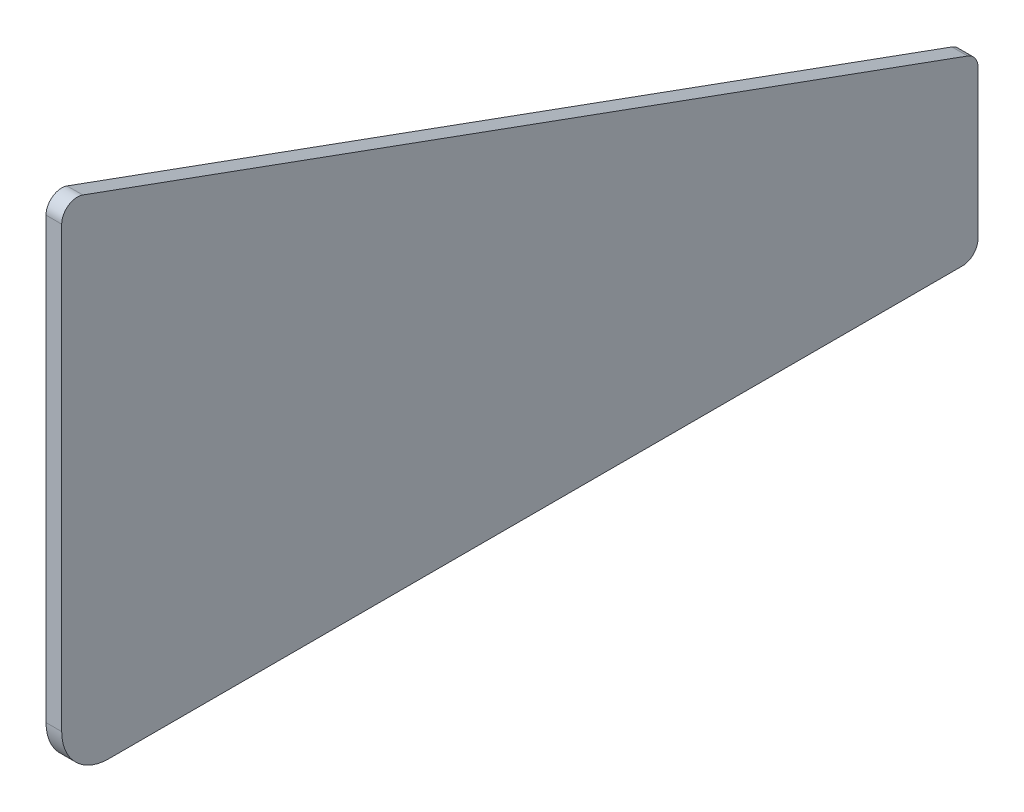
SolidWorks part; units mm, degrees
material "Hexcel AS4C (3000 Filaments)"
ref_plane "Front Plane" through (0, 0, 0) normal (0, 0, 1) x (1, 0, 0)
ref_plane "Top Plane" through (0, 0, 0) normal (0, 1, 0) x (1, 0, 0)
ref_plane "Right Plane" through (0, 0, 0) normal (1, 0, 0) x (0, 0, -1)
sketch "Sketch1" plane through (0, 0, 0) normal (1, 0, 0) x (0, 0, -1)
  line L0 (0, -14.2815) -> (0, -294.2815)
  line L1 (0, 29.2892) -> (0, -29.2892) construction
  line L2 (30, -324.2815) -> (573.8156, -324.2815)
  line L3 (583.8156, -314.2815) -> (583.8156, -219.4936)
  line L4 (577.2358, -210.0966) -> (13.4202, -4.8846)
  arc A0 (30, -324.2815) -> (0, -294.2815) centre (30, -294.2815) cw
  arc A1 (573.8156, -324.2815) -> (583.8156, -314.2815) centre (573.8156, -314.2815) ccw
  arc A2 (583.8156, -219.4936) -> (577.2358, -210.0966) centre (573.8156, -219.4936) ccw
  arc A3 (13.4202, -4.8846) -> (0, -14.2815) centre (10, -14.2815) ccw
  point P9 (0, -324.2815)
  point P16 (0, 0)
  dimension "D2" = 30
  dimension "D3" = 10
  dimension "D1" = 70
  dimension "D4" = 280
  dimension "D5" = 600
extrude "Boss-Extrude1" add sketch "Sketch1" along normal blind 10
sketch "Sketch2" plane through (10, 0, 0) normal (1, 0, 0) x (0, 0, -1)
  arc A0 (23.1622, -218.0173) -> (26.7381, -200.3183) centre (26.5742, -209.4959) cw
  arc A1 (549.474, -291.831) -> (546.1549, -257.731) centre (546.1581, -274.9423) ccw
  arc A2 (26.9502, -47.7372) -> (35.1249, -39.1544) centre (32.8168, -45.1404) cw
  arc A3 (356.3201, -205.3163) -> (353.1695, -171.1817) centre (353.1695, -188.3944) ccw
  spline S0 degree 3 poles (23.1622, -218.0173) (143.0808, -266.0342) (284.6699, -324.5722) (474.7501, -306.5023) (549.474, -291.831) knots 0 0 0 0 0.576112 1 1 1 1
  spline S1 degree 3 poles (26.7381, -200.3183) (45.9144, -200.6608) (151.3211, -255.5104) (414.8803, -286.3851) (542.4311, -257.7317) (546.1549, -257.731) knots 0 0 0 0 0.560935 0.660935 1 1 1 1
  spline S2 degree 3 poles (26.9502, -47.7372) (35.3127, -66.6296) (121.3965, -217.9891) (352.8389, -205.9644) (356.3201, -205.3163) knots 0 0 0 0 0.590315 1 1 1 1
  spline S3 degree 3 poles (35.1249, -39.1544) (50.603, -45.1224) (99.0425, -170.6619) (331.224, -171.1817) (353.1695, -171.1817) knots 0 0 0 0 0.639196 1 1 1 1
sketch "Sketch3" plane through (0, 0, 0) normal (-1, 0, 0) x (0, 0, 1)
  arc A2 (-23.1622, -218.0173) -> (-26.7381, -200.3183) centre (-26.5742, -209.4959) ccw
  arc A3 (-546.1549, -257.731) -> (-549.474, -291.831) centre (-546.1581, -274.9423) ccw
  arc A4 (-23.1622, -218.0173) -> (-26.7381, -200.3183) centre (-26.5742, -209.4959) ccw
  arc A5 (-546.1549, -257.731) -> (-549.474, -291.831) centre (-546.1581, -274.9423) ccw
  arc A6 (-26.9502, -47.7372) -> (-35.1249, -39.1544) centre (-32.8168, -45.1404) ccw
  arc A7 (-353.1695, -171.1817) -> (-356.3201, -205.3163) centre (-353.1695, -188.3944) ccw
  arc A8 (-26.9502, -47.7372) -> (-35.1249, -39.1544) centre (-32.8168, -45.1404) ccw
  arc A9 (-353.1695, -171.1817) -> (-356.3201, -205.3163) centre (-353.1695, -188.3944) ccw
  spline S2 degree 3 poles (-2896.6142, -4288.4219) (3.574, 379.1035) (337.9044, -198.2) (-671.2842, -316.4215) (-1165.7534, 76.4704) (4167.8421, -1921.4128) knots -1.856226 -1.856226 -1.856226 -1.856226 0.560935 0.660935 1.972851 1.972851 1.972851 1.972851 only from (-26.7381, -200.3183) to (-546.1549, -257.731)
  spline S3 degree 3 poles (4297.6783, -1440.9535) (-2101.1476, 528.1742) (-39.3944, -1013.16) (229.8904, 277.3112) (4925.3757, 333.413) knots -3.073366 -3.073366 -3.073366 -3.073366 0.423888 3.006514 3.006514 3.006514 3.006514 only from (-549.474, -291.831) to (-23.1622, -218.0173)
  spline S4 degree 3 poles (-26.7381, -200.3183) (-45.9144, -200.6608) (-151.3211, -255.5104) (-414.8803, -286.3851) (-542.4311, -257.7317) (-546.1549, -257.731) knots 0 0 0 0 0.560935 0.660935 1 1 1 1
  spline S5 degree 3 poles (-549.474, -291.831) (-474.7501, -306.5023) (-284.6699, -324.5722) (-143.0808, -266.0342) (-23.1622, -218.0173) knots 0 0 0 0 0.423888 1 1 1 1
  spline S6 degree 3 poles (1154.6406, -4892.5213) (-500.1842, 847.1931) (679.6519, -597.1648) (-1151.2382, 7.0013) (4611.9466, -753.8783) knots -1.849916 -1.849916 -1.849916 -1.849916 0.639196 2.198 2.198 2.198 2.198 only from (-35.1249, -39.1544) to (-353.1695, -171.1817)
  spline S7 degree 3 poles (4570.7768, -1047.92) (-1095.3741, 46.8314) (476.6072, -749.5305) (-175.5635, 954.0689) (-848.8771, -4973.4503) knots -1.172462 -1.172462 -1.172462 -1.172462 0.409685 2.739203 2.739203 2.739203 2.739203 only from (-356.3201, -205.3163) to (-26.9502, -47.7372)
  spline S8 degree 3 poles (-35.1249, -39.1544) (-50.603, -45.1224) (-99.0425, -170.6619) (-331.224, -171.1817) (-353.1695, -171.1817) knots 0 0 0 0 0.639196 1 1 1 1
  spline S9 degree 3 poles (-356.3201, -205.3163) (-352.8389, -205.9644) (-121.3965, -217.9891) (-35.3127, -66.6296) (-26.9502, -47.7372) knots 0 0 0 0 0.409685 1 1 1 1
  dimension "D1" = 0
  dimension "D2" = 0
extrude "Cut-Extrude3" cut sketch "Sketch3" against normal blind 3
